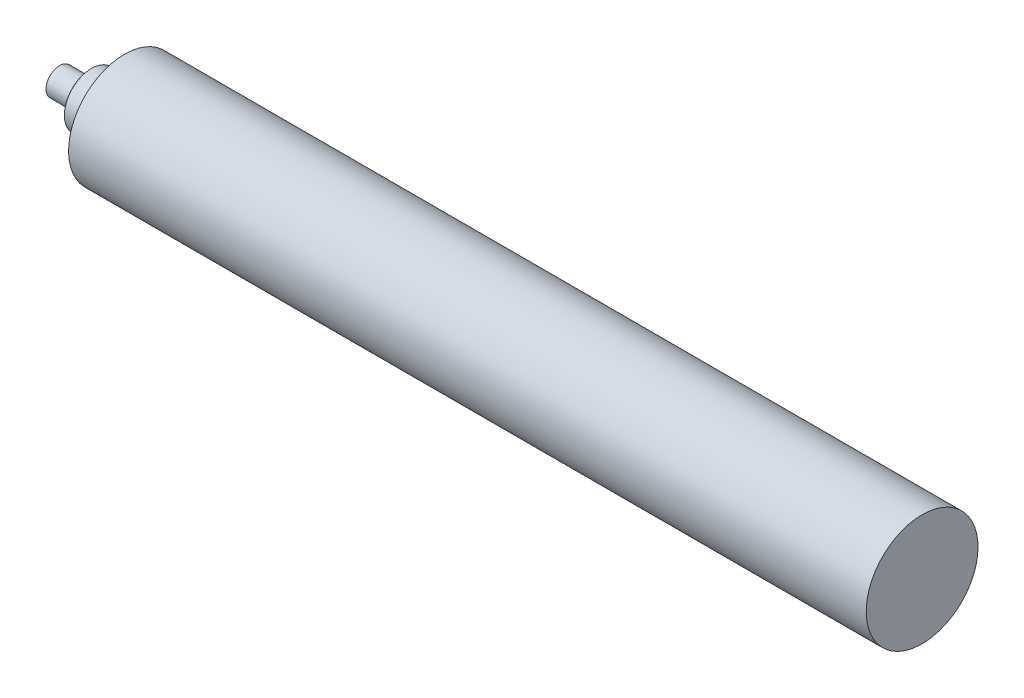
SolidWorks part; units mm, degrees
ref_plane "Front Plane" through (0, 0, 0) normal (0, 0, 1) x (1, 0, 0)
ref_plane "Top Plane" through (0, 0, 0) normal (0, 1, 0) x (1, 0, 0)
ref_plane "Right Plane" through (0, 0, 0) normal (1, 0, 0) x (0, 0, -1)
sketch "Sketch1" plane through (0, 0, 0) normal (0, 0, 1) x (1, 0, 0)
  line L0 (0, 0) -> (0, 11.938)
  line L1 (0, 11.938) -> (24.765, 11.938)
  line L2 (27.305, 14.478) -> (27.305, 22.933)
  line L3 (28.1044, 23.876) -> (57.15, 23.876)
  line L4 (57.15, 23.876) -> (57.15, 49.2125)
  line L5 (57.15, 49.2125) -> (759.206, 49.2125)
  line L6 (759.206, 49.2125) -> (759.206, 0)
  line L7 (759.206, 0) -> (0, 0)
  line L8 (27.305, 22.933) -> (28.1044, 23.876)
  arc A0 (24.765, 11.938) -> (27.305, 14.478) centre (24.765, 14.478) ccw
  point P11 (27.305, 11.938)
  dimension "D1" = 11.938
  dimension "D7" = 2.54
  dimension "D2" = 25.3365
  dimension "D3" = 49.2125
  dimension "D4" = 28.1044
  dimension "D5" = 27.305
  dimension "D6" = 702.056
  dimension "D8" = 57.15
  dimension "D9" = 22.933
revolve "Revolve1" add sketch "Sketch1" angle 360 about L7
sketch "Sketch16" plane through (0, 0, 0) normal (0, 1, 0) x (1, 0, 0)
  line L0 (0, 0) -> (0, 8.3503)
  line L1 (0, 8.3503) -> (1.905, 8.3503) construction
  line L2 (1.905, 8.3503) -> (1.905, 6.5564) construction
  line L3 (1.905, 6.5564) -> (0, 8.3503)
  line L4 (1.905, 6.5564) -> (1.905, 0)
  line L5 (-54.1337, 0) -> (54.1337, 0) construction
  line L6 (1.905, 0) -> (0, 0)
  dimension "D1" = 8.3503
  dimension "D2" = 6.5564
  dimension "D3" = 1.905
revolve "Cut-Revolve1" cut sketch "Sketch16" angle 360 about L6
sketch "Sketch19" plane through (1.905, 0, 0) normal (-1, 0, 0) x (0, 0, 1)
  circle A0 centre (0, 0) radius 4
  dimension "D1" = 8
extrude "Cut-Extrude3" cut sketch "Sketch19" against normal blind 25.4
sketch "Sketch32" plane through (0, 0, 0) normal (0, 1, 0) x (1, 0, 0)
  line L1 (-54.1337, 0) -> (54.1337, 0) construction
  line L2 (27.305, 0) -> (28.575, 0)
  line L3 (27.305, 0) -> (27.305, 6.3511)
  line L4 (27.305, 22.933) -> (27.305, -22.933) construction
  line L5 (27.305, 6.3511) -> (28.575, 0)
  dimension "D1" = 6.3511
  dimension "D2" = 1.27
  dimension "D3" = 27.305
revolve "Cut-Revolve6" cut sketch "Sketch32" angle 360 about L2
